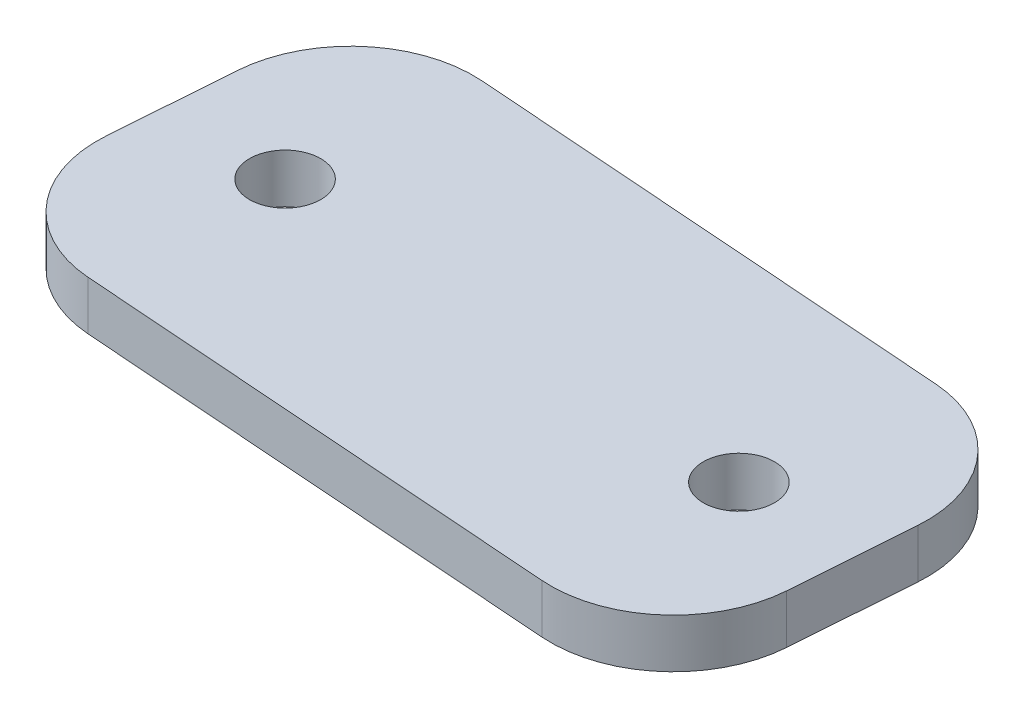
SolidWorks part; units mm, degrees
material "ABS"
ref_plane "前视基准面" through (0, 0, 0) normal (0, 0, 1) x (1, 0, 0)
ref_plane "上视基准面" through (0, 0, 0) normal (0, 1, 0) x (1, 0, 0)
ref_plane "右视基准面" through (0, 0, 0) normal (1, 0, 0) x (0, 0, -1)
other "Configuration Table"
sketch "草图1" plane through (0, 0, 0) normal (0, 1, 0) x (1, 0, 0)
  line L0 (1.0892, 14.9604) -> (0, 0) construction
  line L1 (1.0892, 24.9604) -> (681.0892, 24.9604) construction
  line L2 (1.0892, 24.9604) -> (1.0892, 39.9604) construction
  line L3 (1.0892, 39.9604) -> (681.0892, 39.9604) construction
  line L4 (681.0892, 24.9604) -> (681.0892, 39.9604) construction
  line L5 (1.0892, 14.9604) -> (681.0892, -34.5496) construction
  line L6 (0, 0) -> (680, -49.51) construction
  line L7 (681.0892, -34.5496) -> (680, -49.51) construction
  line L8 (1.0892, 24.9604) -> (1.0892, 14.9604) construction
  line L9 (1.0892, 14.9604) -> (21.0364, 13.5081) construction
  line L10 (21.0364, 13.5081) -> (21.8703, 24.9604) construction
  line L11 (21.8703, 24.9604) -> (1.0892, 24.9604) construction
  line L12 (655.3427, 24.9604) -> (651.1685, -32.3711) construction
  line L13 (651.1685, -32.3711) -> (681.0892, -34.5496) construction
  line L14 (681.0892, -34.5496) -> (681.0892, 24.9604) construction
  line L15 (681.0892, 24.9604) -> (655.3427, 24.9604) construction
  line L16 (571.3797, -26.5618) -> (572.7137, -8.2391) construction
  line L17 (571.3797, -26.5618) -> (-44.6233, -26.5618) construction
  line L18 (646.0892, 39.9604) -> (681.0892, 39.9604) construction
  line L19 (681.0892, 39.9604) -> (681.0892, 24.9604) construction
  line L20 (651.1685, -32.3711) -> (650.0792, -47.3315)
  line L21 (586.0862, 32.4604) -> (718.6857, 32.4604) construction
  line L22 (370.5837, -19.4619) -> (213.1406, -7.9987) construction
  line L23 (666.1289, -33.4604) -> (669.5737, 13.8536) construction
  line L24 (650.0792, -47.3315) -> (680, -49.51)
  line L25 (681.0892, -34.5496) -> (680, -49.51)
  line L26 (21.0364, 13.5081) -> (21.0364, -43.8965) construction
  line L27 (655.3427, 24.9604) -> (646.0892, 24.9604) construction
  line L28 (646.0892, 24.9604) -> (646.0892, 39.9604) construction
  line L29 (681.0892, -34.5496) -> (681.0892, 21.9604) construction
  line L30 (681.0892, 21.9604) -> (666.0892, 21.9604) construction
  line L31 (666.0892, 21.9604) -> (666.0892, 39.9604) construction
  line L32 (666.0892, 39.9604) -> (646.0892, 39.9604) construction
  line L33 (646.0892, 24.9604) -> (652.9839, -7.4371) construction
  line L34 (652.9839, -7.4371) -> (651.1685, -32.3711) construction
  line L35 (651.1685, -32.3711) -> (681.0892, -34.5496)
  circle A0 centre (661.0892, 32.4604) radius 1.45 construction
  circle A1 centre (651.0892, 32.4604) radius 1.45 construction
  circle A2 centre (655.6106, -40.2144) radius 1.45
  circle A3 centre (675.5578, -41.6667) radius 1.45
  circle A4 centre (667.2181, -18.5) radius 1.45 construction
  circle A5 centre (669.3966, 11.4208) radius 1.45 construction
  dimension "D11" = 2.9
  dimension "D1" = 15
  dimension "D2" = 15
  dimension "D3" = 680
  dimension "D4" = 20
  dimension "D5" = 80
  dimension "D6" = 30
  dimension "D7" = 10
  dimension "D8" = 681.8
  dimension "D9" = 7.5
  dimension "D10" = 7.5
  dimension "D12" = 15
  dimension "D13" = 30
  dimension "D14" = 15
  dimension "D15" = 5
  dimension "D16" = 5
  dimension "D17" = 5
  dimension "D18" = 20
  dimension "D19" = 10
  dimension "D20" = 3
  dimension "D21" = 5
  dimension "D22" = 25
extrude "凸台-拉伸1" add sketch "草图1" along normal blind 2
fillet "圆角1" radius 5 4 edges at (651.1685, 1, 32.3711) (681.0892, 1, 34.5496) (680, 1, 49.51) (650.0792, 1, 47.3315)
